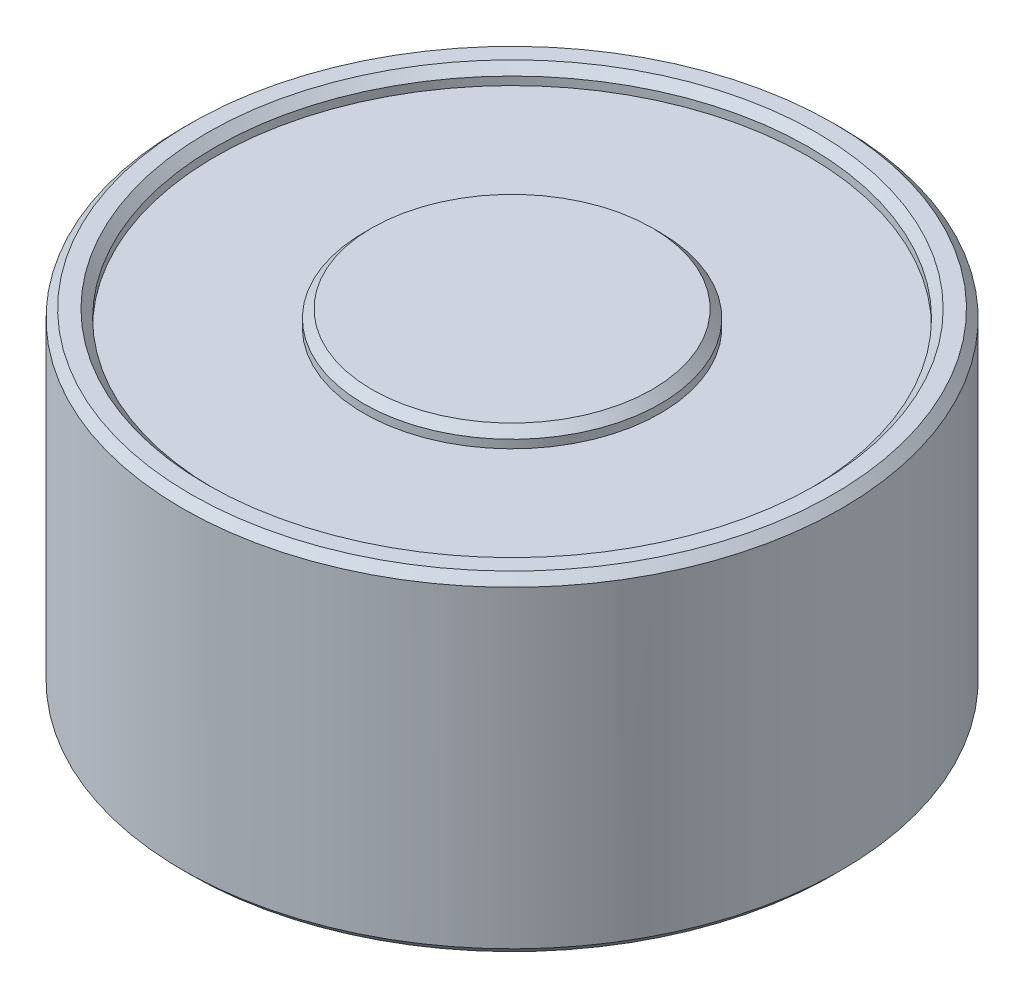
SolidWorks part; units mm, degrees
material "Cast Alloy Steel"
ref_plane "Front" through (0, 0, 0) normal (0, 0, 1) x (1, 0, 0)
ref_plane "Top" through (0, 0, 0) normal (0, 1, 0) x (1, 0, 0)
ref_plane "Right" through (0, 0, 0) normal (1, 0, 0) x (0, 0, -1)
sketch "Sketch1" plane through (0, 0, 0) normal (1, 0, 0) x (0, 0, -1)
  line L0 (0, 0) -> (20, 0)
  line L1 (0, 0) -> (0, 20) construction
  line L2 (20, 0) -> (20, 20)
  line L3 (20, 20) -> (18, 20)
  line L4 (18, 20) -> (18, 19)
  line L5 (18, 19) -> (9, 19)
  line L6 (9, 19) -> (9, 20)
  line L7 (9, 20) -> (0, 20)
  line L8 (0, 0) -> (0, 20)
  dimension "D1" = 40
  dimension "D2" = 20
  dimension "D3" = 18
  dimension "D4" = 2
  dimension "D5" = 1
revolve "Revolve1" add sketch "Sketch1" angle 360 about L1
chamfer "Chamfer1" distance 0.5 angle 45 4 edges at (0, 0, -20) (0, 20, -20) (0, 20, -18) (0, 20, -9)
hole_wizard "M5x0.8 Tapped Hole1" positions "Sketch2" profile "Sketch3" tap size "M5x0.8" standard "ANSI Metric"
sketch "Sketch2" plane through (0, 0, 0) normal (0, -1, 0) x (-1, 0, 0)
  point P0 (0, 0)
sketch "Sketch3" plane through (0, 0, 0) normal (1, 0, 0) x (0, 0, -1)
  line L0 (0, 0) -> (0, 14.4)
  line L1 (0, 14.4) -> (2.1, 13.1382)
  line L2 (2.1, 13.1382) -> (2.1, 0.425)
  line L3 (2.1, 0.425) -> (2.525, 0)
  line L5 (2.525, 0) -> (0, 0)
  line L6 (-2.1, 0.425) -> (-2.525, 0) construction
  line L10 (0, 14.4) -> (-2.1, 13.1382) construction
  line L11 (0, -6.35) -> (0, 107.95) construction
  dimension "Tap Drill Dia." = 4.2
  dimension "Tap Drill Depth" = 14.4
  dimension "Near C'Sink Dia." = 5.05
  dimension "Near C'Sink Angle" = 90
  dimension "Drill Angle" = 118
cosmetic thread "Hole Thread2" parameters "D1"=12, "D2"=5
